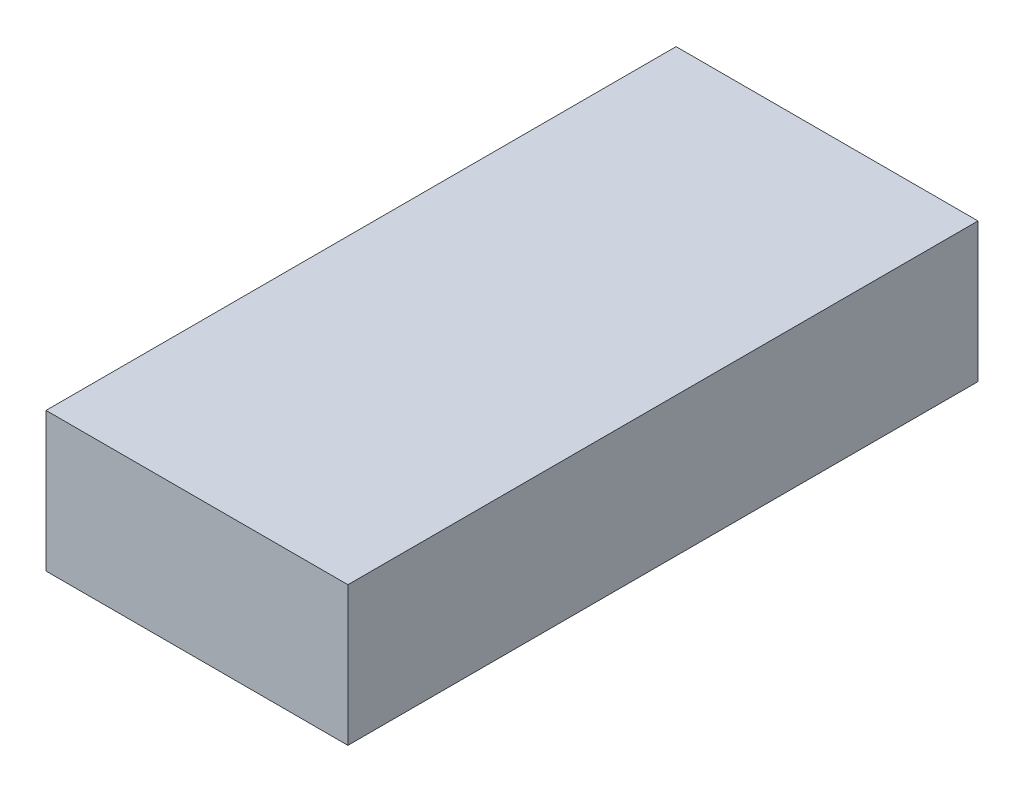
SolidWorks part; units mm, degrees
material "刚性聚氨酯泡沫体"
ref_plane "前视基准面" through (0, 0, 0) normal (0, 0, 1) x (1, 0, 0)
ref_plane "上视基准面" through (0, 0, 0) normal (0, 1, 0) x (1, 0, 0)
ref_plane "右视基准面" through (0, 0, 0) normal (1, 0, 0) x (0, 0, -1)
sketch "草图1" plane through (0, 0, 0) normal (0, 1, 0) x (1, 0, 0)
  line L1 (57.5, -120) -> (-57.5, -120)
  line L2 (57.5, -120) -> (57.5, 120)
  line L3 (57.5, 120) -> (-57.5, 120)
  line L4 (-57.5, -120) -> (-57.5, 120)
  line L5 (57.5, -120) -> (-57.5, 120) construction
  line L6 (57.5, 120) -> (-57.5, -120) construction
  point P0 (0, 0)
extrude "凸台-拉伸1" add sketch "草图1" along normal blind 53
